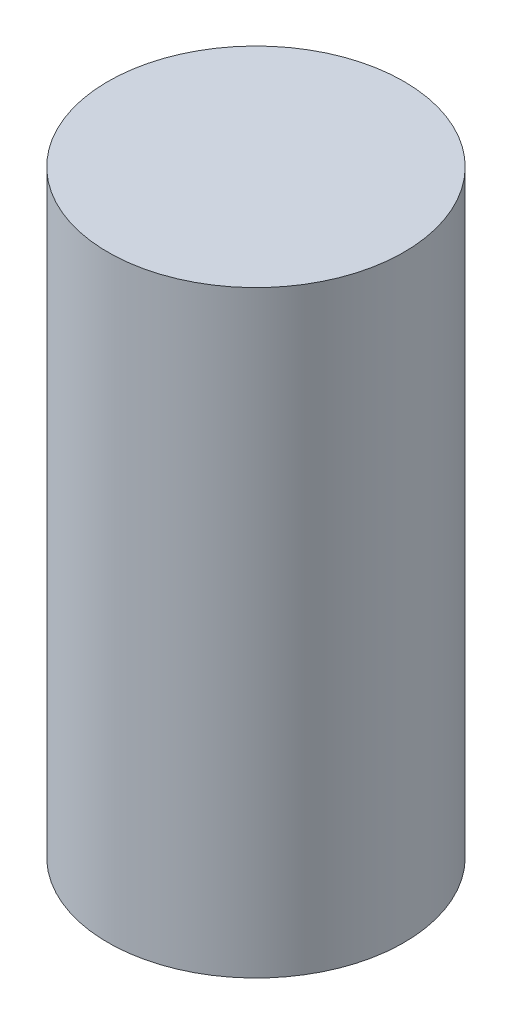
SolidWorks part; units mm, degrees
ref_plane "Plano frontal" through (0, 0, 0) normal (0, 0, 1) x (1, 0, 0)
ref_plane "Plano superior" through (0, 0, 0) normal (0, 1, 0) x (1, 0, 0)
ref_plane "Plano direito" through (0, 0, 0) normal (1, 0, 0) x (0, 0, -1)
sketch "Esboço1" plane through (0, 0, 0) normal (0, 1, 0) x (1, 0, 0)
  circle A0 centre (0, 0) radius 2.45
  dimension "D1" = 4.9
extrude "Ressalto-extrusão1" add sketch "Esboço1" along normal mid plane 9.9
move or copy body "Corpo-Converter em corpo de malha1" [suppressed] bodies to move or copy 101 copy no translate (0, 0, 0) parameters "D1"=0, "D2"=0, "D3"=0
